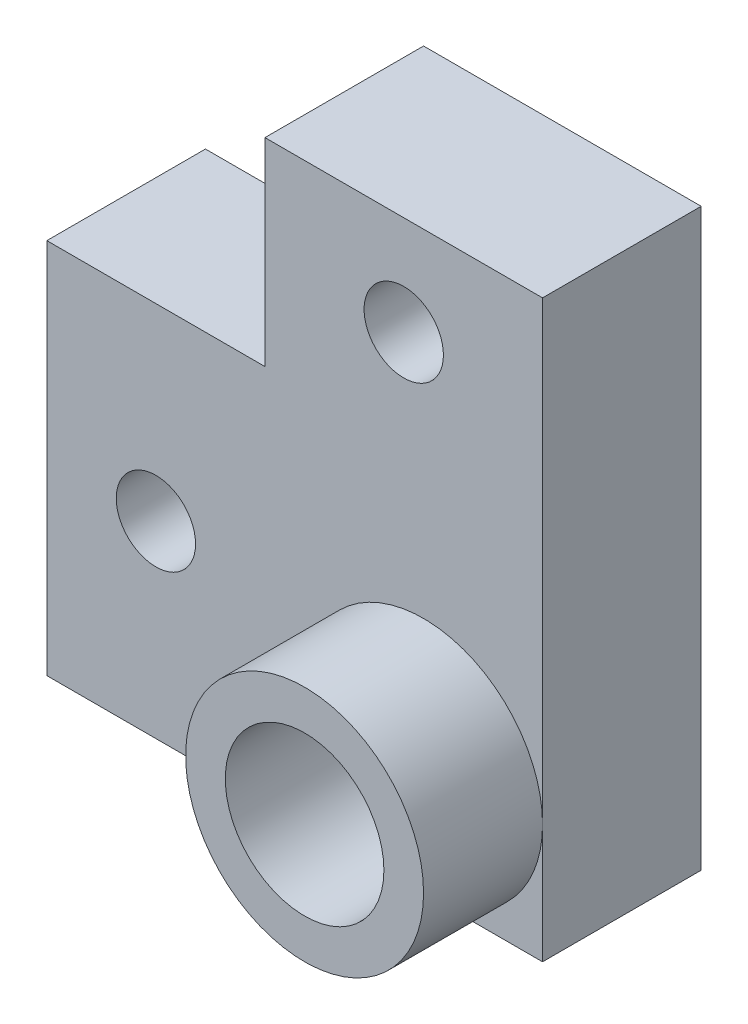
SolidWorks part; units mm, degrees
material "ABS"
ref_plane "Front Plane" through (0, 0, 0) normal (0, 0, 1) x (1, 0, 0)
ref_plane "Top Plane" through (0, 0, 0) normal (0, 1, 0) x (1, 0, 0)
ref_plane "Right Plane" through (0, 0, 0) normal (1, 0, 0) x (0, 0, -1)
sketch "Sketch1" plane through (0, 0, 0) normal (0, 0, 1) x (1, 0, 0)
  line L1 (-12.7947, 11.9139) -> (12.2053, 11.9139)
  line L2 (-12.7947, 11.9139) -> (-12.7947, -7.0861)
  line L3 (-12.7947, -7.0861) -> (12.2053, -7.0861)
  line L4 (12.2053, 11.9139) -> (12.2053, -7.0861)
  dimension "D1" = 19
  dimension "D2" = 25
extrude "Boss-Extrude1" add sketch "Sketch1" along normal blind 8
sketch "Sketch2" plane through (0, 11.9139, 0) normal (0, 1, 0) x (1, 0, 0)
  line L0 (12.2053, 0) -> (-12.7947, 0) construction
  line L1 (12.2053, -8) -> (-1.7947, -8)
  line L2 (12.2053, -8) -> (12.2053, 0)
  line L3 (12.2053, 0) -> (-1.7947, 0)
  line L4 (-1.7947, -8) -> (-1.7947, 0)
  dimension "D1" = 14
extrude "Boss-Extrude2" add sketch "Sketch2" along normal blind 10
sketch "Sketch3" plane through (0, 0, 8) normal (0, 0, 1) x (1, 0, 0)
  line L0 (-1.7947, 11.9139) -> (-12.7947, 11.9139) construction
  line L1 (12.2053, -7.0861) -> (12.2053, 21.9139) construction
  line L2 (-1.7947, 21.9139) -> (12.2053, 21.9139) construction
  line L3 (-12.7947, 11.9139) -> (-12.7947, -7.0861) construction
  circle A0 centre (-7.2947, 2.4139) radius 2
  circle A1 centre (5.2053, 16.9139) radius 2
  dimension "D1" = 4
  dimension "D2" = 4
  dimension "D3" = 9.5
  dimension "D4" = 7
  dimension "D5" = 5
  dimension "D6" = 5.5
extrude "Cut-Extrude1" cut sketch "Sketch3" against normal blind 20
sketch "Sketch4" plane through (0, 0, 8) normal (0, 0, 1) x (1, 0, 0)
  line L0 (12.2053, -7.0861) -> (12.2053, 21.9139) construction
  line L1 (-12.7947, -7.0861) -> (12.2053, -7.0861) construction
  circle A0 centre (6.2053, -1.0861) radius 4
  dimension "D1" = 8
  dimension "D2" = 6
  dimension "D3" = 6
extrude "Cut-Extrude2" cut sketch "Sketch4" against normal blind 20
sketch "Sketch5" plane through (0, 0, 8) normal (0, 0, 1) x (1, 0, 0)
  circle A0 centre (6.2053, -1.0861) radius 6
  circle A1 centre (6.2053, -1.0861) radius 4
  dimension "D1" = 12
extrude "Boss-Extrude3" add sketch "Sketch5" along normal blind 6
